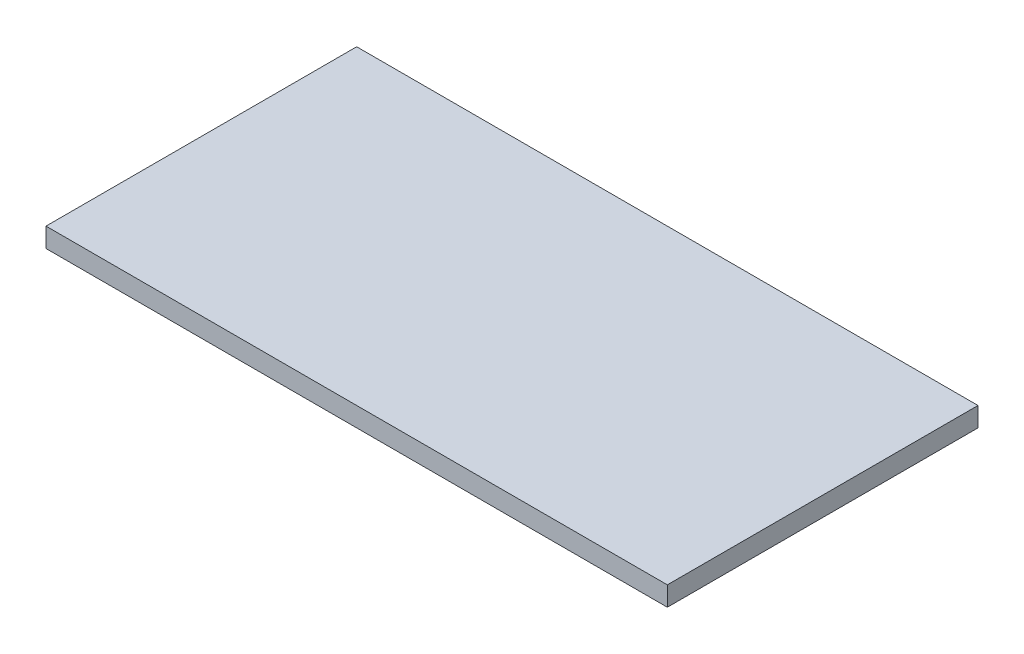
SolidWorks part; units mm, degrees
ref_plane "Front Plane" through (0, 0, 0) normal (0, 0, 1) x (1, 0, 0)
ref_plane "Top Plane" through (0, 0, 0) normal (0, 1, 0) x (1, 0, 0)
ref_plane "Right Plane" through (0, 0, 0) normal (1, 0, 0) x (0, 0, -1)
sketch "Sketch1" plane through (0, 0, 0) normal (0, 1, 0) x (1, 0, 0)
  line L1 (-50.8, 25.4) -> (50.8, 25.4)
  line L2 (-50.8, 25.4) -> (-50.8, -25.4)
  line L3 (-50.8, -25.4) -> (50.8, -25.4)
  line L4 (50.8, 25.4) -> (50.8, -25.4)
  line L5 (-50.8, 25.4) -> (50.8, -25.4) construction
  line L6 (-50.8, -25.4) -> (50.8, 25.4) construction
  point P0 (0, 0)
  dimension "D1" = 50.8
  dimension "D2" = 101.6
extrude "Boss-Extrude1" add sketch "Sketch1" along normal blind 3.175
